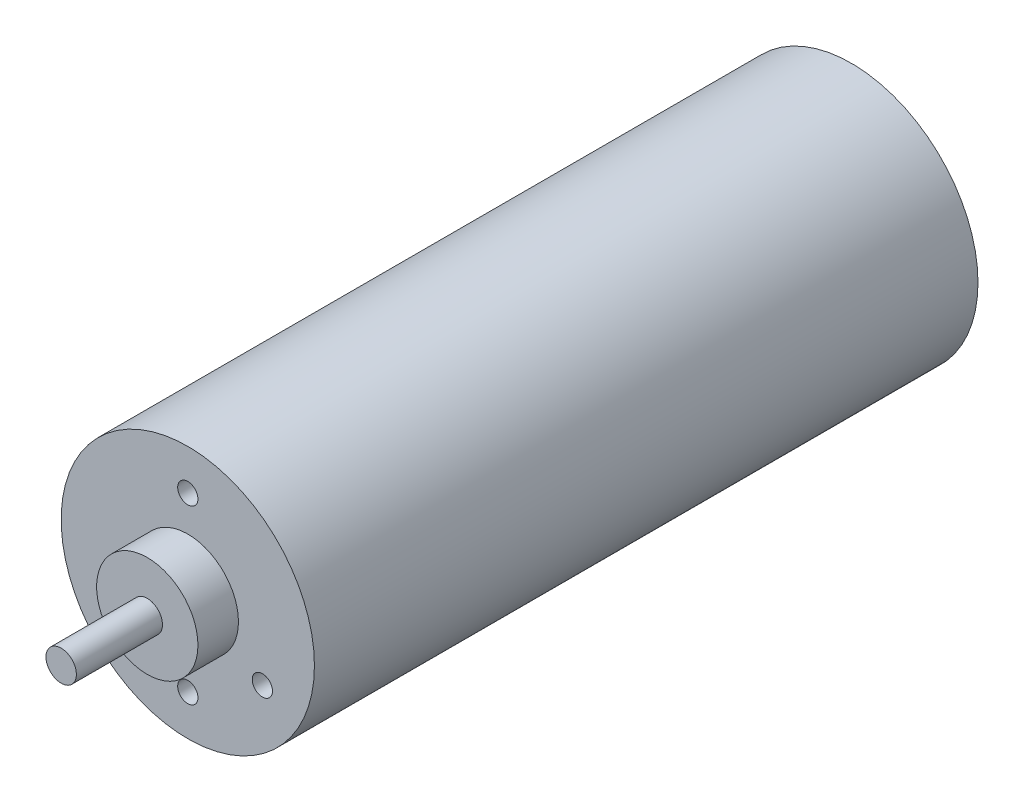
SolidWorks part; units mm, degrees
ref_plane "정면" through (0, 0, 0) normal (0, 0, 1) x (1, 0, 0)
ref_plane "윗면" through (0, 0, 0) normal (0, 1, 0) x (1, 0, 0)
ref_plane "우측면" through (0, 0, 0) normal (1, 0, 0) x (0, 0, -1)
sketch "스케치1" plane through (0, 0, 0) normal (0, 0, 1) x (1, 0, 0)
  circle A0 centre (0, 0) radius 12.5
  dimension "D1" = 25
extrude "돌출1" add sketch "스케치1" along normal blind 65.5
sketch "스케치2" plane through (0, 0, 65.5) normal (0, 0, 1) x (1, 0, 0)
  circle A0 centre (0, 0) radius 5
extrude "돌출2" add sketch "스케치2" along normal blind 4
sketch "스케치3" plane through (0, 0, 65.5) normal (0, 0, 1) x (1, 0, 0)
  circle A0 centre (0, 0) radius 1.5
extrude "돌출3" add sketch "스케치3" along normal blind 12.5
sketch "스케치4" plane through (0, 0, 65.5) normal (0, 0, 1) x (1, 0, 0)
  line L0 (0, 0) -> (0, 8.5) construction
  line L1 (0, 0) -> (0, -8.5) construction
  line L2 (0, 0) -> (-7.3612, -4.25) construction
  line L3 (0, 0) -> (7.3612, -4.25) construction
  circle A0 centre (0, 8.5) radius 1
  circle A1 centre (0, -8.5) radius 1
  circle A2 centre (-7.3612, -4.25) radius 1
  circle A3 centre (7.3612, -4.25) radius 1
  dimension "D1" = 60
  dimension "D2" = 60
extrude "컷-돌출1" cut sketch "스케치4" against normal blind 10
